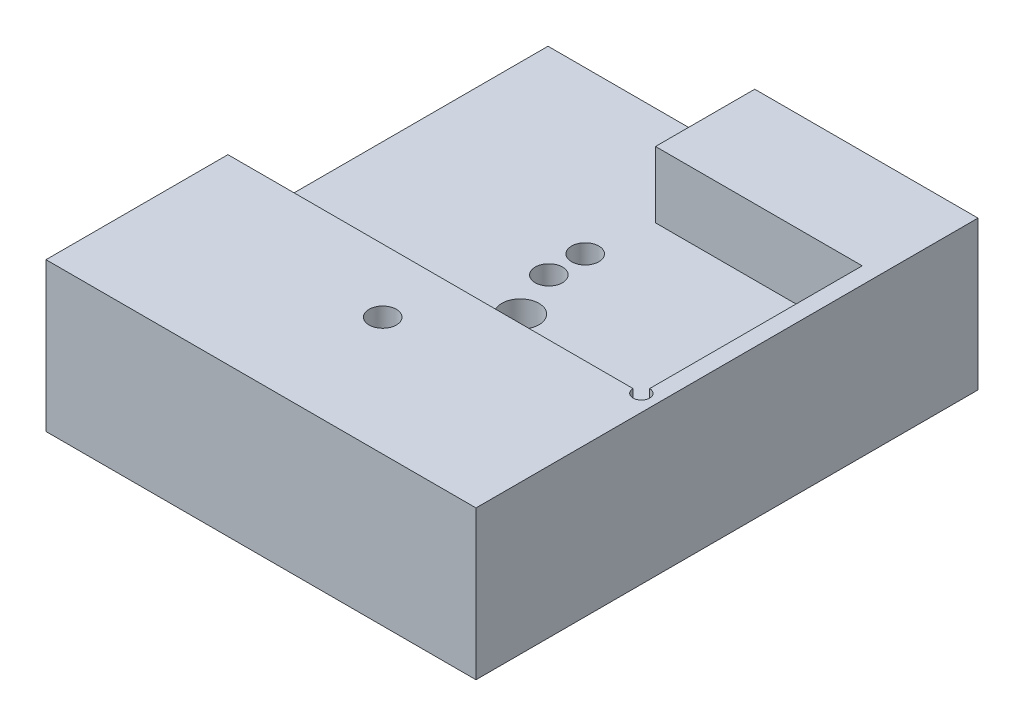
SolidWorks part; units mm, degrees
material "6061 合金"
ref_plane "前视基准面" through (0, 0, 0) normal (0, 0, 1) x (1, 0, 0)
ref_plane "上视基准面" through (0, 0, 0) normal (0, 1, 0) x (1, 0, 0)
ref_plane "右视基准面" through (0, 0, 0) normal (1, 0, 0) x (0, 0, -1)
sketch "草图1" plane through (0, 0, 0) normal (0, 1, 0) x (1, 0, 0)
  line L1 (-25, 13.355) -> (25, 13.355)
  line L2 (-25, 13.355) -> (-25, -13.355)
  line L3 (-25, -13.355) -> (25, -13.355)
  line L4 (25, 13.355) -> (25, -13.355)
  line L5 (-25, 13.355) -> (25, -13.355) construction
  line L6 (-25, -13.355) -> (25, 13.355) construction
  point P0 (0, 0)
  dimension "D1" = 50
  dimension "D2" = 26.71
extrude "凸台-拉伸1" add sketch "草图1" along normal blind 6
sketch "草图2" plane through (0, 6, 0) normal (0, 1, 0) x (1, 0, 0)
  line L1 (25, 13.355) -> (-25, 13.355) construction
  line L3 (25, 13.355) -> (-25, 13.355)
  line L12 (-25, -13.355) -> (25, -13.355) construction
  line L13 (-25, -13.355) -> (25, -13.355)
  line L19 (25, -13.355) -> (25, 13.355) construction
  line L20 (25, -13.355) -> (25, 13.355)
  line L21 (-25, -15.355) -> (27, -15.355)
  line L22 (27, -15.355) -> (27, 15.355)
  line L23 (27, 15.355) -> (-25, 15.355)
  line L24 (-25, -15.355) -> (-25, -13.355)
  line L25 (-25, 13.355) -> (-25, 15.355)
  dimension "D1" = 2
extrude "凸台-拉伸2" add sketch "草图2" along normal blind 8 and the other way through all
sketch "草图3" plane through (0, 6, 0) normal (0, 1, 0) x (1, 0, 0)
  line L0 (-1, 13.355) -> (-1, 5.855) construction
  line L1 (25, -13.355) -> (25, 13.355) construction
  line L3 (25, 13.355) -> (-25, 13.355) construction
  line L5 (-1, 5.855) -> (25, 5.855) construction
  circle A0 centre (-1, 5.855) radius 1.3881
  point P6 (0, 0)
  point P7 (0, 0)
  point P10 (51, 5.85)
  dimension "D1" = 7.5
  dimension "D2" = 26
hole_wizard "M4 螺纹孔1" positions "3D草图1" profile "草图4" tap size "M4" standard "GB"
sketch3d "3D草图1"
  point P0 (-1, 6, -5.855)
sketch "草图4" plane through (-1, 6, -5.855) normal (1, 0, 0) x (0, 0, 1)
  line L0 (0, 0) -> (0, 11.0914)
  line L1 (0, 11.0914) -> (1.65, 10.1)
  line L2 (1.65, 10.1) -> (1.65, 0)
  line L5 (1.65, 0) -> (0, 0)
  line L10 (0, 11.0914) -> (-1.65, 10.1) construction
  line L11 (0, -6.35) -> (0, 107.95) construction
  dimension "螺纹孔钻头直径" = 3.3
  dimension "螺纹孔钻头深度" = 10.1
  dimension "导头角度" = 118
cosmetic thread "孔螺蚊线1" parameters "D1"=2.4, "D2"=4
sketch "草图12" plane through (-25, 0, 0) normal (-1, 0, 0) x (0, 0, 1)
  line L1 (-13.355, 6) -> (-15.355, 6)
  line L2 (-13.355, 6) -> (-13.355, 14)
  line L3 (-13.355, 14) -> (-15.355, 14)
  line L4 (-15.355, 6) -> (-15.355, 14)
extrude "切除-拉伸5" cut sketch "草图12" against normal blind 25
sketch "草图24" plane through (0, 0, -15.355) normal (0, 0, -1) x (-1, 0, 0)
  line L6 (25, 6) -> (0, 6)
  line L7 (0, 6) -> (0, 14)
  line L8 (0, 14) -> (-27, 14)
  line L9 (-27, 14) -> (-27, 0)
  line L10 (-27, 0) -> (25, 0)
  line L11 (25, 0) -> (25, 6)
  line L12 (25, 6) -> (0, 6)
  line L13 (0, 6) -> (0, 14)
  line L14 (0, 14) -> (-27, 14)
  line L15 (-27, 14) -> (-27, 0)
  line L16 (-27, 0) -> (25, 0)
  line L17 (25, 0) -> (25, 6)
  dimension "D1" = 0
extrude "凸台-拉伸5" add sketch "草图24" along normal blind 10
sketch "草图25" plane through (0, 0, 15.355) normal (0, 0, 1) x (1, 0, 0)
  line L4 (27, 0) -> (27, 14)
  line L5 (27, 14) -> (-25, 14)
  line L6 (-25, 14) -> (-25, 0)
  line L7 (-25, 0) -> (27, 0)
  line L8 (27, 0) -> (27, 14)
  line L9 (27, 14) -> (-25, 14)
  line L10 (-25, 14) -> (-25, 0)
  line L11 (-25, 0) -> (27, 0)
  dimension "D1" = 0
extrude "凸台-拉伸6" add sketch "草图25" along normal blind 20
sketch "草图13" plane through (0, 14, 0) normal (0, 1, 0) x (1, 0, 0)
  circle A0 centre (25, -13.355) radius 1
extrude "切除-拉伸6" cut sketch "草图13" against normal up to surface (8 mm away)
sketch "草图5" plane through (0, 0, 0) normal (0, -1, 0) x (1, 0, 0)
  line L1 (-13.5, 11.045) -> (11.5, 11.045)
  line L2 (-13.5, 11.045) -> (-13.5, -13.955)
  line L3 (-13.5, -13.955) -> (11.5, -13.955)
  line L4 (11.5, 11.045) -> (11.5, -13.955)
  line L5 (-13.5, 11.045) -> (11.5, -13.955) construction
  line L6 (-13.5, -13.955) -> (11.5, 11.045) construction
  circle A0 centre (-1, -1.455) radius 1.1939
  circle A2 centre (-1, -5.855) radius 1.65 construction
  point P0 (-1, 3.3617)
  dimension "D3" = 4.4
  dimension "D1" = 25
  dimension "D2" = 25
extrude "切除-拉伸1" cut sketch "草图5" against normal blind 2
sketch "草图6" plane through (0, 2, 0) normal (0, -1, 0) x (1, 0, 0)
  line L0 (-1, 11.045) -> (-1, -13.955) construction
  line L3 (-1, -1.455) -> (-13.5, -1.455) construction
  line L6 (-13.5, 11.045) -> (-13.5, -13.955) construction
  line L8 (11.5, 11.045) -> (-13.5, 11.045) construction
  point P2 (0.6724, 16.7641)
  point P3 (-12.0622, 6.565)
  point P4 (0, 0)
  point P5 (0, 0)
  point P8 (-8.49, 12.555)
  point P9 (0, 0)
  point P12 (0, 0)
  point P14 (0, 0)
  dimension "D1" = 25
  dimension "D2" = 12.5
hole_wizard "M4 螺纹孔2" positions "3D草图2" profile "草图7" tap size "M4" standard "GB" end condition through all
sketch3d "3D草图2"
  point P0 (-1, 2, -1.455)
cosmetic thread "孔螺蚊线2" parameters "D2"=4
sketch "草图7" plane through (-1, 2, -1.455) normal (1, 0, 0) x (0, 0, -1)
  line L0 (0, 0) -> (0, 12)
  line L1 (0, 12) -> (1.65, 12)
  line L2 (1.65, 12) -> (1.65, 0)
  line L5 (1.65, 0) -> (0, 0)
  line L11 (0, -6.35) -> (0, 107.95) construction
  dimension "通孔螺纹孔钻头直径" = 3.3
  dimension "通孔螺纹孔钻头深度" = 12
sketch "草图14" plane through (0, 0, 0) normal (0, -1, 0) x (1, 0, 0)
  line L5 (27, 35.355) -> (-25, 35.355)
  line L6 (-13.5, 11.045) -> (-13.5, -13.955)
  line L7 (-13.5, -13.955) -> (11.5, -13.955)
  line L8 (11.5, -13.955) -> (11.5, 11.045)
  line L9 (11.5, 11.045) -> (-13.5, 11.045)
  line L10 (-13.5, 11.045) -> (-13.5, -13.955)
  line L11 (27, 35.355) -> (-25, 35.355)
  line L12 (-25, 35.355) -> (-25, -25.355)
  line L13 (-25, -25.355) -> (27, -25.355)
  line L14 (27, -25.355) -> (27, 35.355)
  line L20 (-25, 35.355) -> (-25, -25.355)
  line L22 (27, -25.355) -> (27, 35.355)
  line L24 (11.5, -13.955) -> (11.5, 11.045)
  line L25 (11.5, 11.045) -> (-13.5, 11.045)
  line L27 (-13.5, -13.955) -> (11.5, -13.955)
  line L30 (-25, -25.355) -> (27, -25.355)
  dimension "D1" = 0
  dimension "D2" = 0
extrude "凸台-拉伸3" add sketch "草图14" along normal blind 4
sketch "草图16" plane through (0, -4, 0) normal (0, -1, 0) x (1, 0, 0)
  line L1 (-11.12, 33.865) -> (13.88, 33.865)
  line L2 (-11.12, 33.865) -> (-11.12, 8.865)
  line L3 (-11.12, 8.865) -> (13.88, 8.865)
  line L4 (13.88, 33.865) -> (13.88, 8.865)
  line L5 (-11.12, 33.865) -> (13.88, 8.865) construction
  line L6 (-11.12, 8.865) -> (13.88, 33.865) construction
  point P0 (1.38, 21.365)
  point P6 (0, 0)
  point P8 (1.38, -6.235)
  point P9 (1.378, -6.235)
  point P10 (1.378, -7.3695)
  point P11 (1.378, 12.3035)
  dimension "D1" = 25
  dimension "D2" = 25
  dimension "D3" = 22.82
  dimension "D4" = 2.38
extrude "切除-拉伸7" cut sketch "草图16" against normal blind 1.84
sketch "草图26" plane through (0, -4, 0) normal (0, -1, 0) x (1, 0, 0)
  circle A0 centre (1.378, 4.3695) radius 2.5
  circle A2 centre (-1, -5.855) radius 1.3881 construction
  point P4 (0, 0)
  point P6 (-1, -5.855)
  dimension "D1" = 1.3881
  dimension "D2" = 10.2245
hole_wizard "打孔尺寸(%根据)内六角圆柱头螺钉的类型0" positions "3D草图4" profile "草图27" counterbore size "M4" standard "GB" end condition through all
sketch3d "3D草图4"
  point P0 (1.378, -4, 4.3695)
sketch "草图27" plane through (1.378, -4, 4.3695) normal (1, 0, 0) x (0, 0, -1)
  line L0 (0, 0) -> (0, 18)
  line L1 (0, 18) -> (2.25, 18)
  line L3 (2.25, 18) -> (2.25, 4.6)
  line L4 (2.25, 4.6) -> (4, 4.6)
  line L5 (4, 4.6) -> (4, 0)
  line L7 (4, 0) -> (0, 0)
  line L11 (0, -6.35) -> (0, 107.95) construction
  dimension "通孔孔直径" = 4.5
  dimension "通孔孔深度" = 18
  dimension "柱形沉头孔直径" = 8
  dimension "柱形沉头孔深度" = 4.6
sketch "草图28" plane through (0, -2.16, 0) normal (0, -1, 0) x (1, 0, 0)
  line L0 (1.38, 33.865) -> (1.38, 21.0159) construction
  line L1 (13.88, 33.865) -> (-11.12, 33.865) construction
hole_wizard "M4 螺纹孔3" positions "3D草图5" profile "草图29" tap size "M4" standard "GB" end condition through all
sketch3d "3D草图5"
  point P0 (1.38, -2.16, 21.0159)
sketch "草图29" plane through (1.38, -2.16, 21.0159) normal (1, 0, 0) x (0, 0, -1)
  line L0 (0, 0) -> (0, 16.16)
  line L1 (0, 16.16) -> (1.65, 16.16)
  line L2 (1.65, 16.16) -> (1.65, 0)
  line L5 (1.65, 0) -> (0, 0)
  line L11 (0, -6.35) -> (0, 107.95) construction
  dimension "通孔螺纹孔钻头直径" = 3.3
  dimension "通孔螺纹孔钻头深度" = 16.16
cosmetic thread "孔螺蚊线3" parameters "D2"=4
